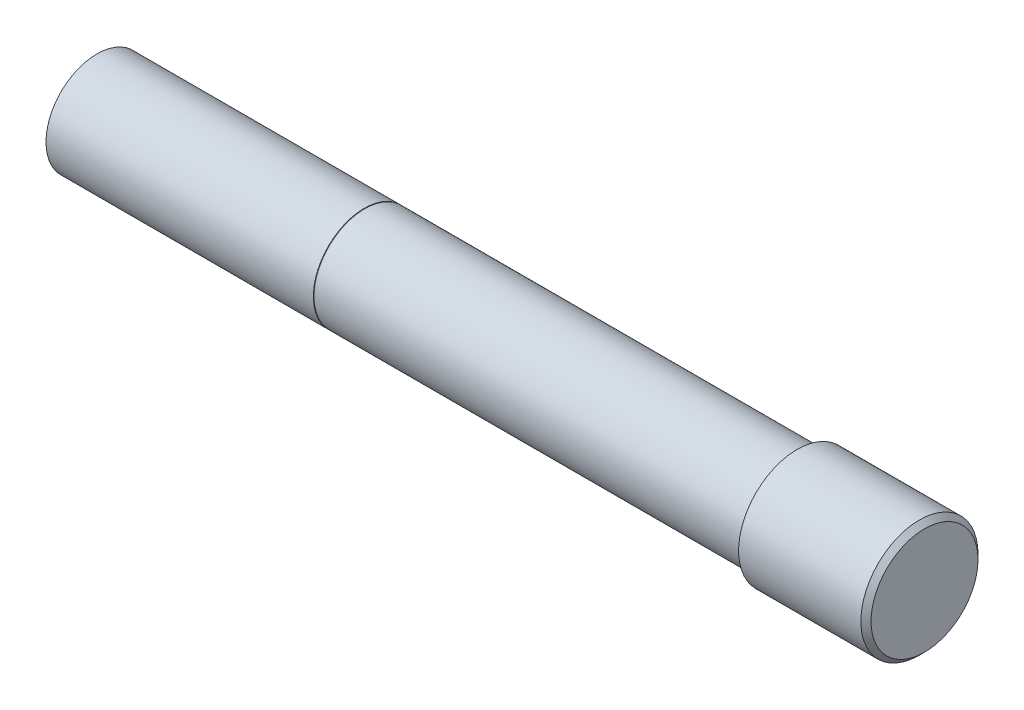
SolidWorks part; units mm, degrees
material "AISI 1020"
ref_plane "Plano superior" through (0, 0, 0) normal (0, 0, 1) x (1, 0, 0)
ref_plane "Plano frontal" through (0, 0, 0) normal (0, 1, 0) x (1, 0, 0)
ref_plane "Plano direito" through (0, 0, 0) normal (1, 0, 0) x (0, 0, -1)
sketch "Esboço1" plane through (0, 0, 0) normal (0, 1, 0) x (1, 0, 0)
  line L0 (0, 0) -> (33, 0)
  line L1 (33, 0) -> (33, 2.3)
  line L2 (33, 2.3) -> (28, 2.3)
  line L3 (28, 2.3) -> (28, 2)
  line L4 (28, 2) -> (11.0296, 2)
  line L5 (0, 2) -> (0, 0)
  line L6 (0, 0) -> (-0.7726, 0) construction
  line L8 (11, 2) -> (0, 2)
  line L11 (11, 2) -> (11, 1.982)
  line L12 (11, 1.982) -> (11.0296, 1.982)
  line L13 (11.0296, 2) -> (11.0296, 1.982)
  dimension "D1" = 2
  dimension "D2" = 2.3
  dimension "D3" = 5
  dimension "D4" = 33
revolve "Revolução1" add sketch "Esboço1" angle 360 about L6
cosmetic thread "Representação de rosca3" parameters "D2"=3.22
cosmetic thread "Representação de rosca4" parameters "D1"=10.5, "D2"=3.22
cosmetic thread "Representação de rosca5" parameters "D1"=10.5, "D2"=3.22
chamfer "Chanfro1" distance 0.2 angle 45 1 edges at (33, 0, -2.3)
sketch "Esboço5" plane through (0, 0, 0) normal (-1, 0, 0) x (0, 0, 1)
  circle A0 centre (0, 0) radius 2.6273
extrude "Corte-extrusão1" cut sketch "Esboço5" against normal blind 0.5
